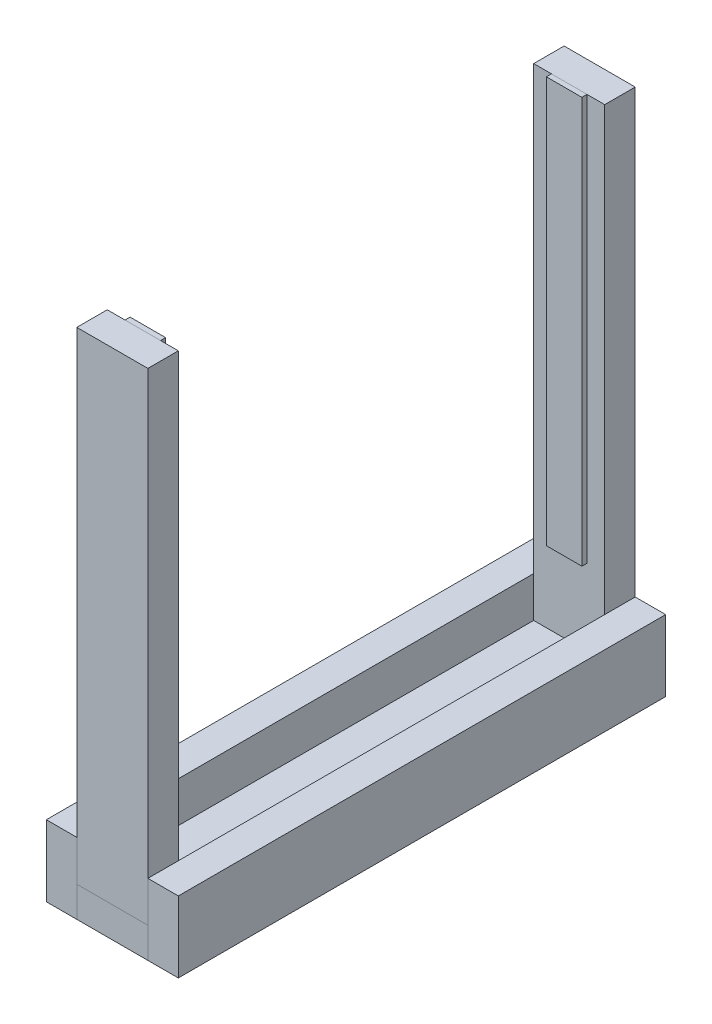
SolidWorks part; units mm, degrees
material "Oak"
ref_plane "Front Plane" through (0, 0, 0) normal (0, 0, 1) x (1, 0, 0)
ref_plane "Top Plane" through (0, 0, 0) normal (0, 1, 0) x (1, 0, 0)
ref_plane "Right Plane" through (0, 0, 0) normal (1, 0, 0) x (0, 0, -1)
sketch "Sketch1" plane through (0, 0, 0) normal (0, 1, 0) x (1, 0, 0)
  line L1 (-44.45, -304.8) -> (44.45, -304.8)
  line L2 (-44.45, -304.8) -> (-44.45, 304.8)
  line L3 (-44.45, 304.8) -> (44.45, 304.8)
  line L4 (44.45, -304.8) -> (44.45, 304.8)
  line L5 (-44.45, -304.8) -> (44.45, 304.8) construction
  line L6 (-44.45, 304.8) -> (44.45, -304.8) construction
  point P0 (0, 0)
  dimension "D1" = 609.6
  dimension "D2" = 88.9
extrude "Base Board" add sketch "Sketch1" along normal blind 38.1
sketch "Sketch2" plane through (0, 38.1, 0) normal (0, 1, 0) x (1, 0, 0)
  line L0 (-44.45, 304.8) -> (-44.45, -304.8) construction
  line L1 (44.45, -304.8) -> (-44.45, -304.8)
  line L2 (44.45, -304.8) -> (44.45, -266.7)
  line L3 (44.45, -266.7) -> (-44.45, -266.7)
  line L4 (-44.45, -304.8) -> (-44.45, -266.7)
  dimension "D1" = 38.1
extrude "Vertical Board" add sketch "Sketch2" along normal blind 603.25 separate body
mirror "Vertical Board Mirror" about plane through (0, 0, 0) normal (0, 0, 1) of bodies 102
sketch "Sketch3" plane through (44.45, 0, 0) normal (1, 0, 0) x (0, 0, -1)
  line L0 (304.8, 641.35) -> (304.8, 38.1) construction
  line L1 (-304.8, 0) -> (304.8, 0)
  line L2 (-304.8, 0) -> (-304.8, 88.9)
  line L3 (-304.8, 88.9) -> (304.8, 88.9)
  line L4 (304.8, 0) -> (304.8, 88.9)
  dimension "D1" = 88.9
extrude "Lateral Support" add sketch "Sketch3" along normal blind 38.1 separate body
mirror "Lateral Support Mirror" about plane through (0, 0, 0) normal (1, 0, 0) of bodies 104
sketch "Sketch4" plane through (0, 0, 266.7) normal (0, 0, -1) x (-1, 0, 0)
  line L0 (-44.45, 641.35) -> (44.45, 641.35) construction
  line L1 (-22.225, 641.35) -> (22.225, 641.35)
  line L2 (-22.225, 641.35) -> (-22.225, 133.35)
  line L3 (-22.225, 133.35) -> (22.225, 133.35)
  line L4 (22.225, 641.35) -> (22.225, 133.35)
  point P6 (0, 641.35)
  dimension "D1" = 508
  dimension "D2" = 44.45
extrude "Drawer Slide" add sketch "Sketch4" along normal blind 6.35 separate body
mirror "Drawer Slide Mirror" about plane through (0, 0, 0) normal (0, 0, 1) of bodies 106
